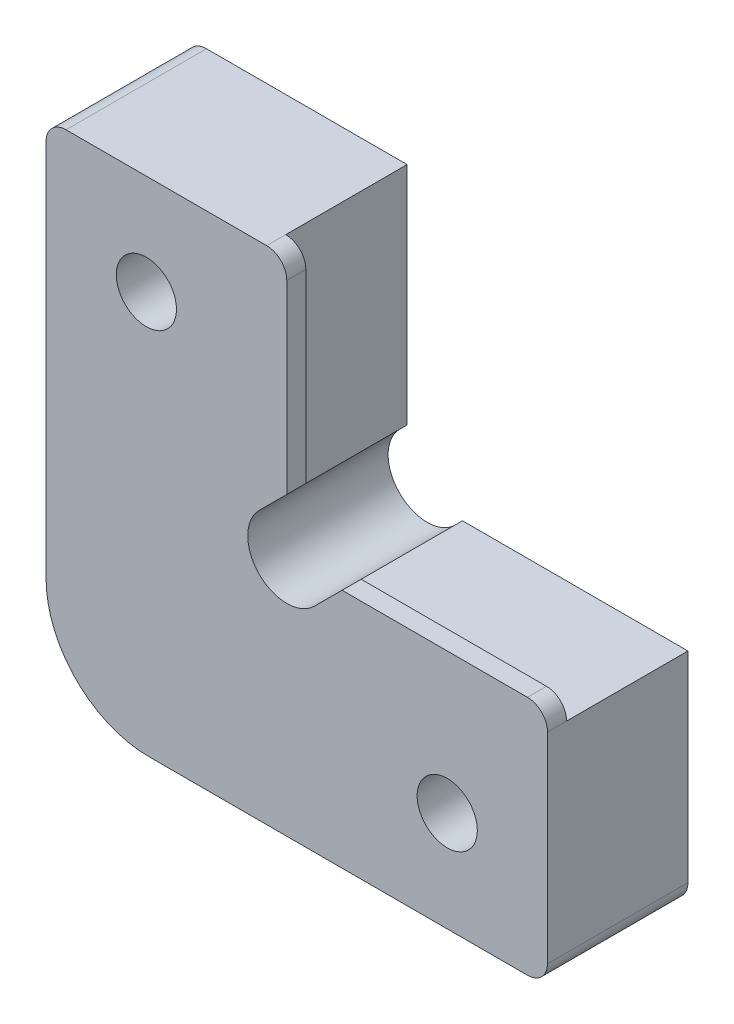
SolidWorks part; units mm, degrees
ref_plane "Front Plane" through (0, 0, 0) normal (0, 0, 1) x (1, 0, 0)
ref_plane "Top Plane" through (0, 0, 0) normal (0, 1, 0) x (1, 0, 0)
ref_plane "Right Plane" through (0, 0, 0) normal (1, 0, 0) x (0, 0, -1)
sketch "Sketch1" plane through (0, 0, 0) normal (0, 0, 1) x (1, 0, 0)
  line L0 (-11, 13.0037) -> (-11, -5.8678)
  line L1 (-5.8678, -11) -> (13.0037, -11)
  line L2 (-10.0037, 14) -> (0, 14)
  line L3 (14, -10.0037) -> (14, 0)
  line L4 (14, 0) -> (2.7577, 0)
  line L7 (2.3826, -0.3751) -> (2.7577, 0)
  line L8 (0, 14) -> (14, 0) construction
  line L9 (2.1024, -1) -> (6.1024, -1) construction
  line L10 (0, 2.7577) -> (-0.3751, 2.3826)
  line L11 (0, 2.7577) -> (0, 14)
  line L12 (-10.7082, 13.7082) -> (-8.4227, 15.9937) construction
  line L13 (-4.9393, 7.9393) -> (-3.3447, 9.534) construction
  line L14 (7.9393, -4.9393) -> (9.5033, -3.3754) construction
  arc A0 (-11, -5.8678) -> (-5.8678, -11) centre (-5.8678, -5.8678) ccw
  arc A1 (-10.0037, 14) -> (-11, 13.0037) centre (-10.0037, 13.0037) ccw
  arc A2 (13.0037, -11) -> (14, -10.0037) centre (13.0037, -10.0037) ccw
  arc A6 (-0.3751, 2.3826) -> (2.3826, -0.3751) centre (1.0037, 1.0037) ccw
  circle A7 centre (9, -6) radius 1.5
  circle A8 centre (-6, 9) radius 1.5
  point P9 (9, -7.5)
  point P11 (-0.3751, -0.3751)
  point P25 (-7.5, 9)
  point P26 (-6, 10.5)
  point P27 (10.5, -6)
  point P32 (-9.4968, -9.4968)
  dimension "D11" = 3
  dimension "D16" = 0.9963
  dimension "D1" = 25
  dimension "D2" = 11
  dimension "D5" = 135
  dimension "D6" = 4
  dimension "D7" = 10
  dimension "D8" = 23.33
  dimension "D3" = 3.9
  dimension "D4" = 12.9
  dimension "D9" = 15.315
  dimension "D10" = 3.5
  dimension "D12" = 3.5
  dimension "D13" = 3.5
  dimension "D14" = 3.5
  dimension "D15" = 18.2132
extrude "Boss-Extrude1" add sketch "Sketch1" along normal blind 7
sketch "Sketch2" plane through (0, 0, 7) normal (0, 0, 1) x (1, 0, 0)
  line L0 (2.7577, 0) -> (3.7577, 1)
  line L1 (3.7577, 1) -> (13, 1)
  line L2 (0, 2.7577) -> (1, 3.7577)
  line L3 (1, 3.7577) -> (1, 13)
  line L4 (-0.3751, 2.3826) -> (0, 2.7577) construction
  line L5 (2.7577, 0) -> (2.3826, -0.3751) construction
  line L6 (-11, 13.0037) -> (-11, -5.8678) construction
  line L7 (0, 14) -> (-10.0037, 14) construction
  line L9 (14, -10.0037) -> (14, 0) construction
  line L10 (0, 14) -> (0, 2.7577)
  line L11 (2.7577, 0) -> (14, 0)
  arc A1 (0, 14) -> (1, 13) centre (0, 13) cw
  arc A2 (14, 0) -> (13, 1) centre (13, 0) ccw
  dimension "D1" = 12
extrude "Boss-Extrude2" add sketch "Sketch2" against normal blind 0.95
equation "\"D12@Sketch1\"=\"D10@Sketch1\""
equation "\"D14@Sketch1\"=\"D13@Sketch1\""
